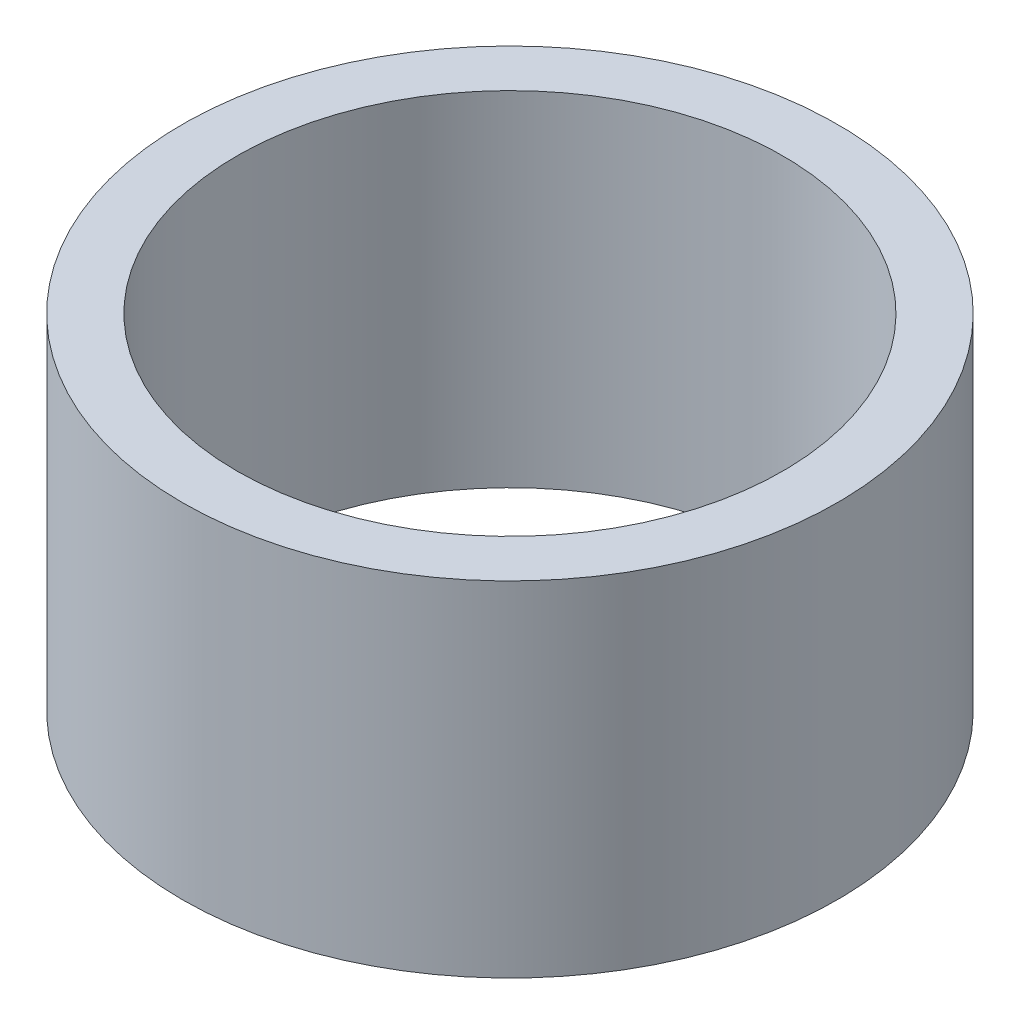
SolidWorks part; units mm, degrees
material "Custom Plastic"
ref_plane "X-Y Datum" through (0, 0, 0) normal (0, 0, 1) x (1, 0, 0)
ref_plane "X-Z Datum" through (0, 0, 0) normal (0, 1, 0) x (1, 0, 0)
ref_plane "Y-Z Datum" through (0, 0, 0) normal (1, 0, 0) x (0, 0, -1)
sketch "Sketch1" plane through (0, 0, 0) normal (0, 1, 0) x (1, 0, 0)
  circle A0 centre (0, 0) radius 3.9687
  circle A1 centre (0, 0) radius 4.7625
  dimension "D1" = 7.9375
  dimension "D2" = 9.525
extrude "Boss-Extrude1" add sketch "Sketch1" along normal blind 5
